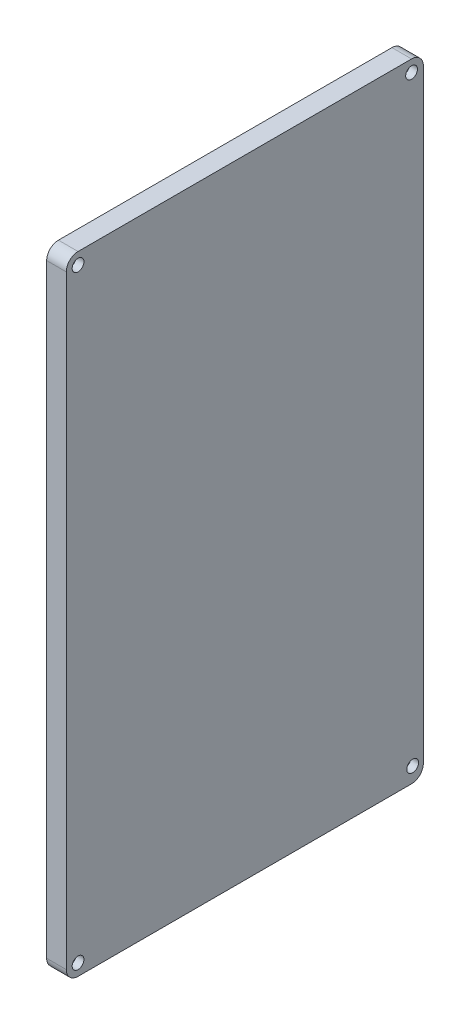
SolidWorks part; units mm, degrees
ref_plane "Front Plane" through (0, 0, 0) normal (0, 0, 1) x (1, 0, 0)
ref_plane "Top Plane" through (0, 0, 0) normal (0, 1, 0) x (1, 0, 0)
ref_plane "Right Plane" through (0, 0, 0) normal (1, 0, 0) x (0, 0, -1)
sketch "Sketch1" plane through (0, 0, 0) normal (1, 0, 0) x (0, 0, -1)
  line L1 (-45.5, -80) -> (45.5, -80)
  line L2 (-45.5, -80) -> (-45.5, 80)
  line L3 (-45.5, 80) -> (45.5, 80)
  line L4 (45.5, -80) -> (45.5, 80)
  line L5 (-45.5, -80) -> (45.5, 80) construction
  line L6 (-45.5, 80) -> (45.5, -80) construction
  point P0 (0, 0)
  dimension "D1" = 91
  dimension "D2" = 160
extrude "Boss-Extrude1" add sketch "Sketch1" against normal blind 5
fillet "Fillet1" radius 3 4 edges at (-2.5, -80, -45.5) (-2.5, -80, 45.5) (-2.5, 80, -45.5) (-2.5, 80, 45.5)
sketch "Sketch2" plane through (-5, 0, 0) normal (-1, 0, 0) x (0, 0, 1)
  line L0 (-42.5, 80) -> (42.5, 80) construction
  line L1 (-45.5, -77) -> (-45.5, 77) construction
  line L2 (45.5, 77) -> (45.5, -77) construction
  circle A0 centre (-42.7746, -76.1956) radius 2.5
  circle A1 centre (42.5, -77) radius 2.5
  circle A2 centre (42.5, 77) radius 2.5
  circle A3 centre (-42.5, 77) radius 2.5
  dimension "D1" = 5
  dimension "D2" = 3
  dimension "D3" = 3
  dimension "D4" = 3
  dimension "D5" = 3
extrude "Cut-Extrude1" cut sketch "Sketch2" against normal blind 3
sketch "Sketch3" plane through (-2, 0, 0) normal (-1, 0, 0) x (0, 0, 1)
  circle A0 centre (-42.5, 77) radius 1.5
  circle A1 centre (42.5, 77) radius 1.5
  circle A2 centre (42.5, -77) radius 1.5
  circle A3 centre (-42.7746, -76.1956) radius 1.5
  dimension "D1" = 3
extrude "Cut-Extrude2" cut sketch "Sketch3" against normal blind 5
